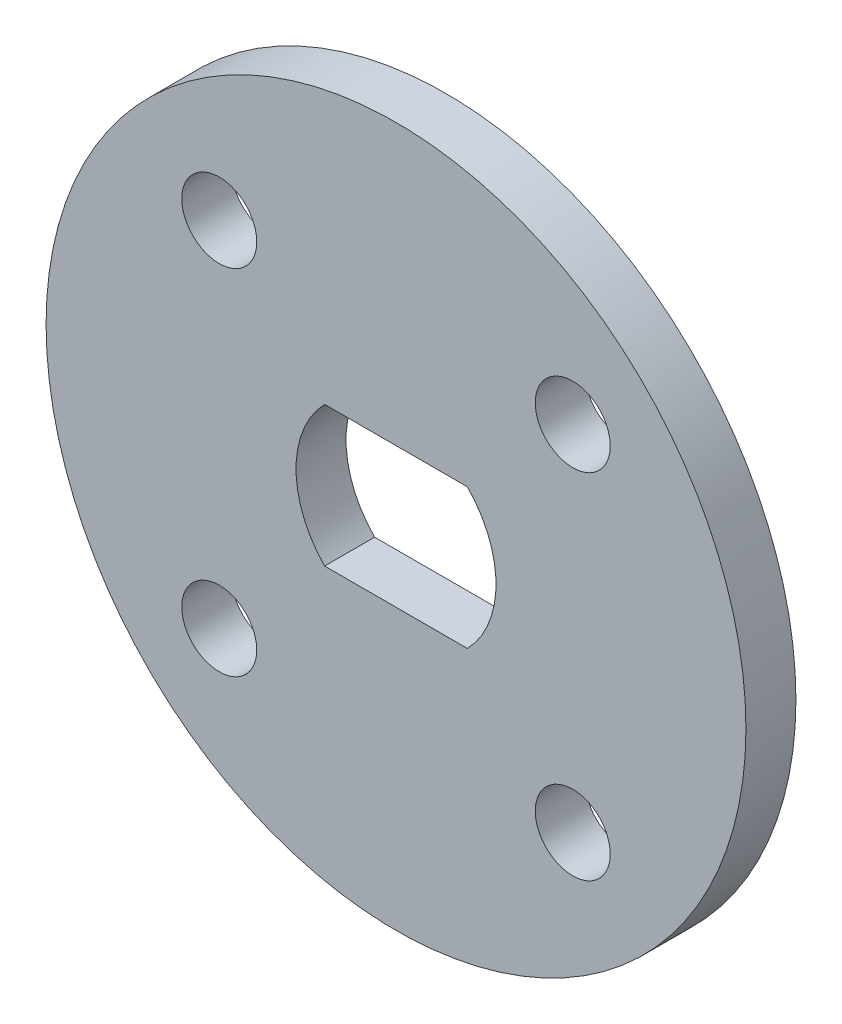
SolidWorks part; units mm, degrees
ref_plane "前视基准面" through (0, 0, 0) normal (0, 0, 1) x (1, 0, 0)
ref_plane "上视基准面" through (0, 0, 0) normal (0, 1, 0) x (1, 0, 0)
ref_plane "右视基准面" through (0, 0, 0) normal (1, 0, 0) x (0, 0, -1)
sketch "草图1" plane through (0, 0, 0) normal (0, 0, 1) x (1, 0, 0)
  circle A1 centre (0, 0) radius 14
  circle A3 centre (-7.0711, 7.0711) radius 1.5
  circle A4 centre (7.0711, 7.0711) radius 1.5
  circle A5 centre (-7.0711, -7.0711) radius 1.5
  circle A6 centre (7.0711, -7.0711) radius 1.5
extrude "凸台-拉伸1" add sketch "草图1" along normal blind 2
sketch "草图2" plane through (0, 0, 0) normal (0, 0, -1) x (-1, 0, 0)
  line L9 (-2.6885, -2.8) -> (2.6885, -2.8)
  line L10 (-2.8566, 2.8) -> (2.8566, 2.8)
  line L14 (-2.8566, -2.8) -> (2.8566, -2.8)
  arc A1 (-2.8566, 2.8) -> (-2.8566, -2.8) centre (0, 0) ccw
  arc A2 (2.8566, 2.8) -> (2.8566, -2.8) centre (0, 0) cw
extrude "切除-拉伸1" cut sketch "草图2" against normal through all contours A2 L10 A1 L9
